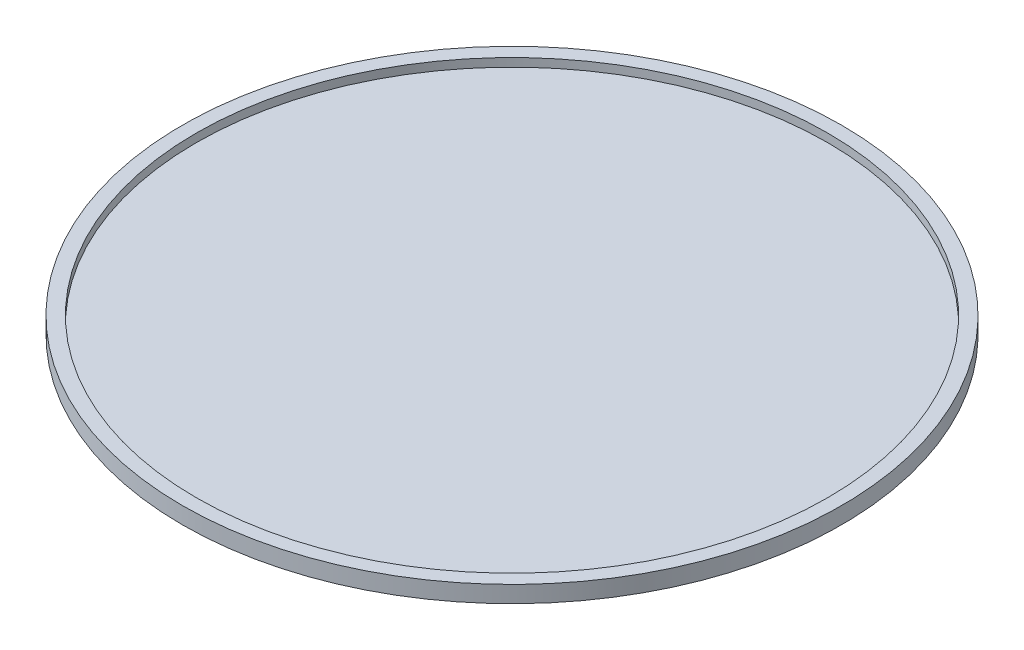
SolidWorks part; units mm, degrees
ref_plane "Front Plane" through (0, 0, 0) normal (0, 0, 1) x (1, 0, 0)
ref_plane "Top Plane" through (0, 0, 0) normal (0, 1, 0) x (1, 0, 0)
ref_plane "Right Plane" through (0, 0, 0) normal (1, 0, 0) x (0, 0, -1)
sketch "Sketch1" plane through (0, 0, 0) normal (0, 1, 0) x (1, 0, 0)
  circle A0 centre (0, 0) radius 100.33
  dimension "D1" = 200.66
extrude "Boss-Extrude1" add sketch "Sketch1" along normal blind 5.08
sketch "Sketch2" plane through (0, 5.08, 0) normal (0, 1, 0) x (1, 0, 0)
  circle A0 centre (0, 0) radius 96.139
  dimension "D1" = 192.278
extrude "Cut-Extrude1" cut sketch "Sketch2" against normal blind 2.54 contours A0
